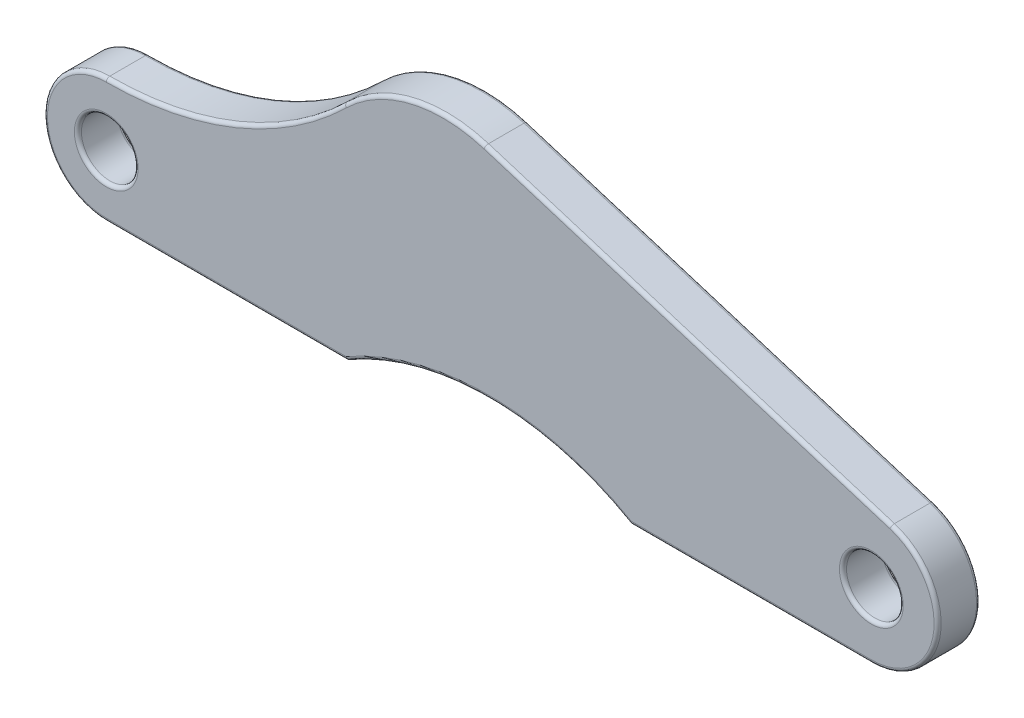
SolidWorks part; units mm, degrees
ref_plane "Front Plane" through (0, 0, 0) normal (0, 0, 1) x (1, 0, 0)
ref_plane "Top Plane" through (0, 0, 0) normal (0, 1, 0) x (1, 0, 0)
ref_plane "Right Plane" through (0, 0, 0) normal (1, 0, 0) x (0, 0, -1)
sketch "Sketch1" plane through (0, 0, 0) normal (0, 0, 1) x (1, 0, 0)
  line L0 (-27, 0) -> (27, 0) construction
  line L1 (-27, 0) -> (-10, 0)
  line L2 (10, 0) -> (27, 0)
  line L3 (28.3871, 9.1448) -> (-0.2635, 18.041)
  arc A0 (-10, 0) -> (10, 0) centre (0, -17.3205) cw
  arc A1 (-27, 0) -> (-27, 8.8) centre (-27, 4.4) cw
  arc A3 (-0.2635, 18.041) -> (-10.2204, 15.6406) centre (-3.2289, 8.4908) ccw
  arc A4 (-10.2204, 15.6406) -> (-27, 8.8) centre (-27, 32.8) cw
  arc A5 (27, 0) -> (28.3871, 9.1448) centre (27, 4.6776) ccw
  circle A6 centre (27, 4.6776) radius 2
  circle A7 centre (-27, 4.4) radius 2
  dimension "D4" = 4.4
  dimension "D5" = 20
  dimension "D7" = 10
  dimension "D8" = 24
  dimension "D10" = 4
  dimension "D1" = 54
  dimension "D2" = 17
  dimension "D3" = 17
  dimension "D6" = 17.25
  dimension "D9" = 30
extrude "Boss-Extrude1" add sketch "Sketch1" along normal mid plane 3
fillet "Fillet1" radius 0.25 20 edges at (29, 4.6776, 1.5) (-25, 4.4, 1.5) (-17.9398, 10.5758, 1.5) (-5.5726, 18.2123, 1.5) (14.0618, 13.5929, 1.5) (31.6247, 3.9761, 1.5) (18.5, 0, 1.5) (0, 2.6795, 1.5) (-18.5, 0, 1.5) (-31.4, 4.4, 1.5) (29, 4.6776, -1.5) (-18.5, 0, -1.5) (0, 2.6795, -1.5) (18.5, 0, -1.5) (31.6247, 3.9761, -1.5) (14.0618, 13.5929, -1.5) (-5.5726, 18.2123, -1.5) (-17.9398, 10.5758, -1.5) (-31.4, 4.4, -1.5) (-25, 4.4, -1.5)
